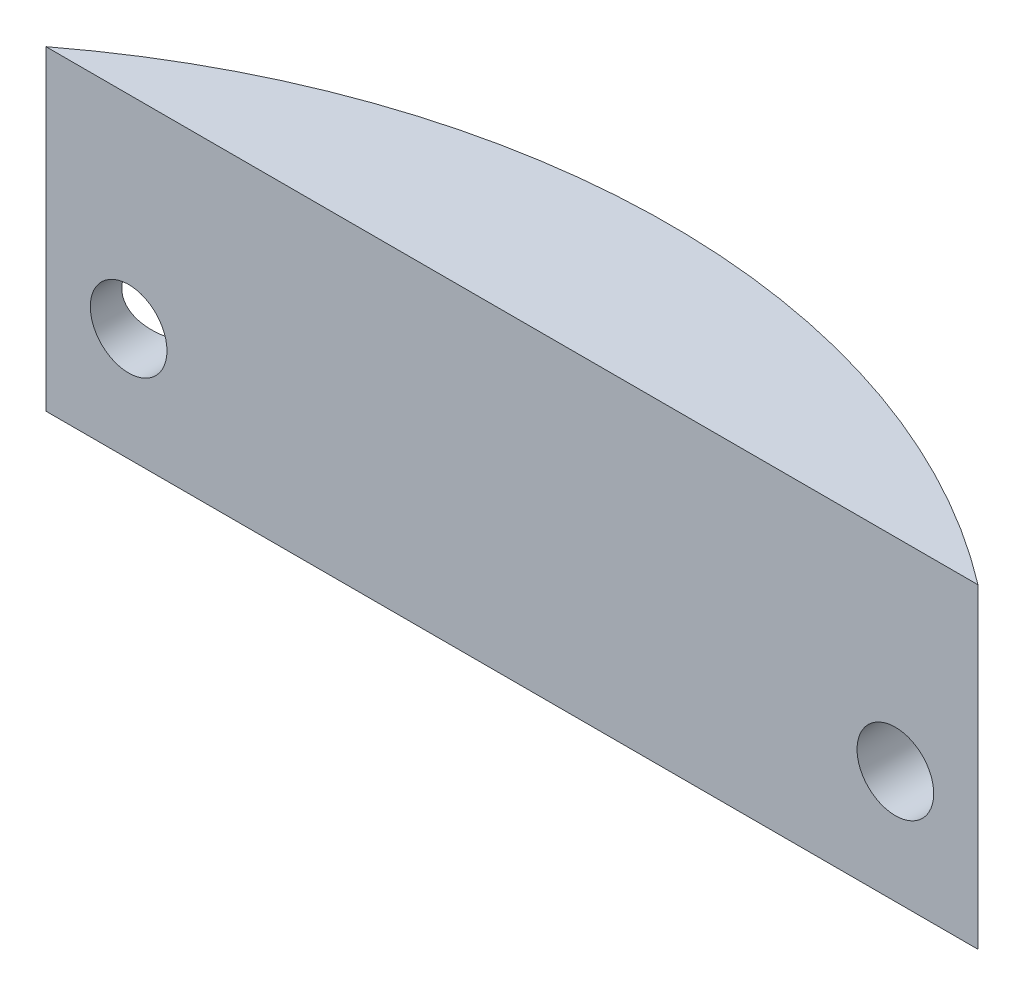
SolidWorks part; units mm, degrees
ref_plane "Front Plane" through (0, 0, 0) normal (0, 0, 1) x (1, 0, 0)
ref_plane "Top Plane" through (0, 0, 0) normal (0, 1, 0) x (1, 0, 0)
ref_plane "Right Plane" through (0, 0, 0) normal (1, 0, 0) x (0, 0, -1)
sketch "Sketch1" plane through (0, 0, 0) normal (0, 1, 0) x (1, 0, 0)
  line L0 (-51.6599, 67.5) -> (51.6599, 67.5)
  arc A0 (-51.6599, 67.5) -> (51.6599, 67.5) centre (0, 0) cw
  dimension "D1" = 67.5
  dimension "D2" = 85
extrude "Boss-Extrude1" add sketch "Sketch1" along normal blind 35
sketch "Sketch2" plane through (0, 0, -67.5) normal (0, 0, 1) x (1, 0, 0)
  line L0 (0, 52.8627) -> (0, -34.1258) construction
  line L2 (-51.6599, 35) -> (51.6599, 35) construction
  circle A0 centre (-42.5, 12.5) radius 4.25
  circle A1 centre (42.5, 12.5) radius 4.25
  dimension "D3" = 8.5
  dimension "D4" = 8.5
  dimension "D1" = 85
  dimension "D2" = 22.5
extrude "Cut-Extrude1" cut sketch "Sketch2" against normal blind 10
